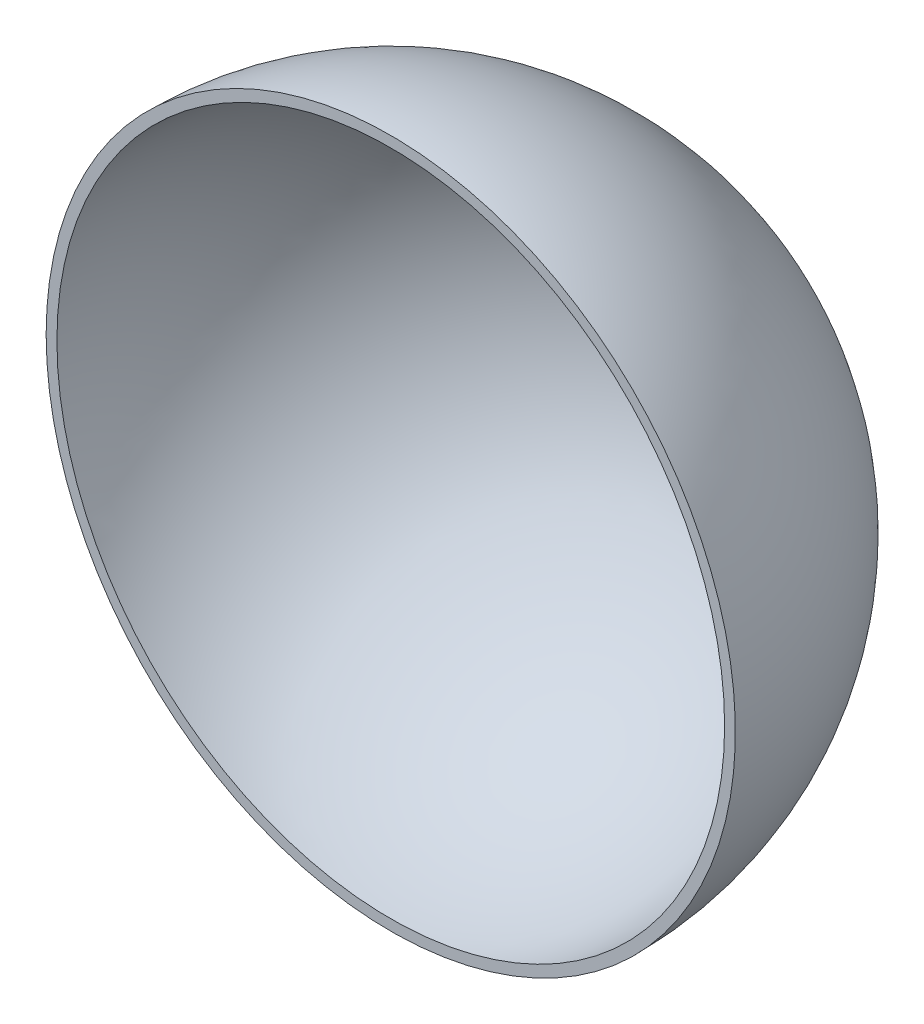
SolidWorks part; units mm, degrees
material "A-Glass Fiber"
ref_plane "Front Plane" through (0, 0, 0) normal (0, 0, 1) x (1, 0, 0)
ref_plane "Top Plane" through (0, 0, 0) normal (0, 1, 0) x (1, 0, 0)
ref_plane "Right Plane" through (0, 0, 0) normal (1, 0, 0) x (0, 0, -1)
sketch "Sketch1" plane through (0, 0, 0) normal (0, 0, 1) x (1, 0, 0)
  line L0 (0, 0) -> (0, 320) construction
  line L1 (0, 310) -> (0, 320)
  line L2 (0, -310) -> (0, -320)
  arc A2 (0, 320) -> (0, -320) centre (0, 0) ccw
  arc A3 (0, 310) -> (0, -310) centre (0, 0) ccw
revolve "Revolve5" add sketch "Sketch1" angle 180 about L2
